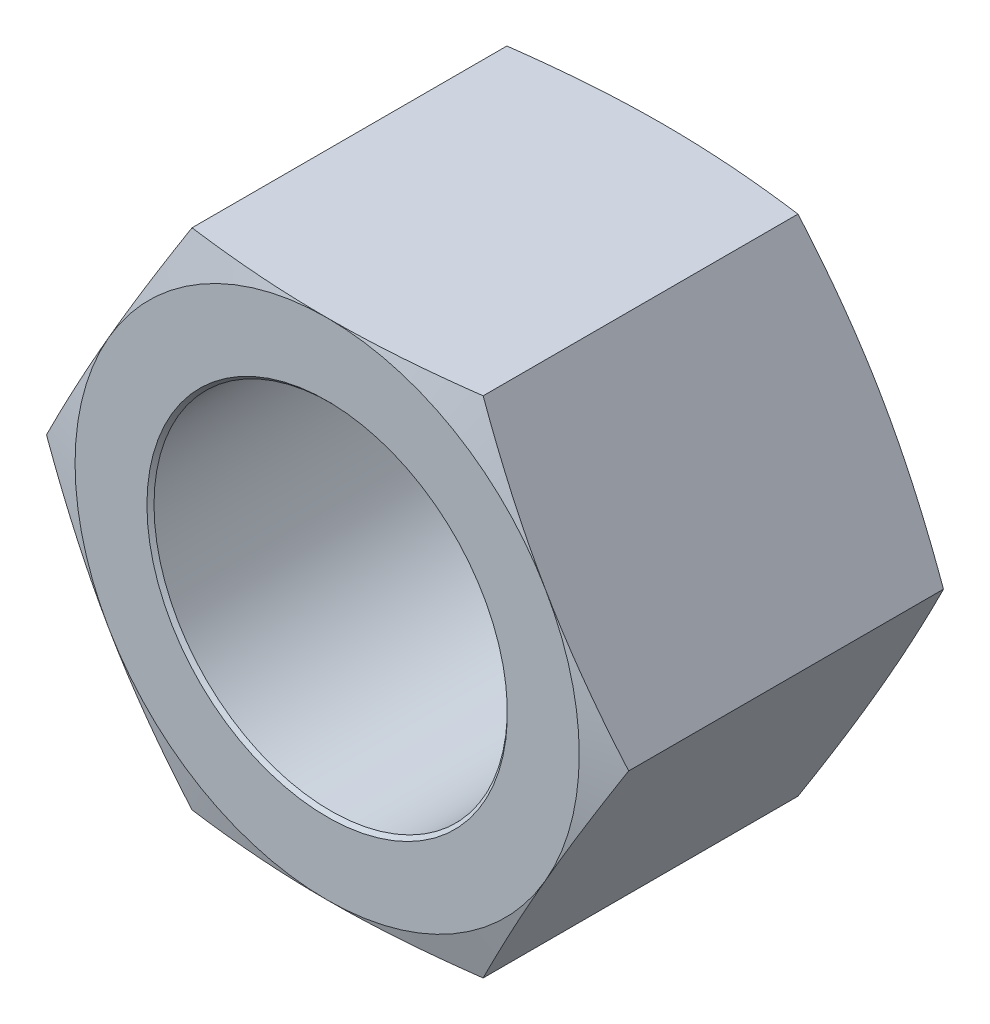
SolidWorks part; units mm, degrees
ref_plane "基准面1" through (0, 0, 0) normal (0, 0, 1) x (1, 0, 0)
ref_plane "基准面2" through (0, 0, 0) normal (0, 1, 0) x (1, 0, 0)
ref_plane "基准面3" through (0, 0, 0) normal (1, 0, 0) x (0, 0, -1)
sketch "尺寸草图" plane through (0, 0, 0) normal (0, 0, 1) x (1, 0, 0)
  line L0 (0, 0) -> (24.1005, 0)
  point P3 (20, 0)
  point P4 (1.5, 0)
  point P5 (32.95, 0)
  point P6 (19, 0)
  point P7 (6.4, 0)
  point P8 (30, 0)
  dimension "D" = 20
  dimension "e" = 32.95
  dimension "P1" = 1.5
  dimension "m" = 19
  dimension "mw" = 6.4
  dimension "s" = 30
sketch "草图1" plane through (0, 0, 0) normal (0, 0, 1) x (1, 0, 0)
  line L0 (-26.8088, 0) -> (37.1748, 0) construction
  line L1 (0, 25.0215) -> (0, -25.0215) construction
  line L3 (8.2375, 14.2678) -> (-8.2375, 14.2678)
  line L4 (-8.2375, 14.2678) -> (-16.475, 0)
  line L5 (-16.475, 0) -> (-8.2375, -14.2678)
  line L6 (-8.2375, -14.2678) -> (8.2375, -14.2678)
  line L7 (8.2375, -14.2678) -> (16.475, 0)
  line L8 (16.475, 0) -> (8.2375, 14.2678)
  circle A0 centre (0, 0) radius 14.2678 construction
  circle A1 centre (0, 0) radius 10
  dimension "D" = 20
  dimension "e" = 32.95
extrude "基体-拉伸" add sketch "草图1" along normal blind 19
cosmetic thread "装饰螺纹线1" parameters "D2"=21
sketch "草图2" plane through (0, 0, 0) normal (0, 0, -1) x (-1, 0, 0)
  line L0 (-8.2375, 14.2678) -> (8.2375, 14.2678) construction
  circle A0 centre (0, 0) radius 14.2678
  circle A1 centre (0, 0) radius 10 construction
extrude "切除-拉伸1" cut sketch "草图2" against normal blind 38 draft 75 flip side to cut
sketch "草图3" plane through (0, 0, 19) normal (0, 0, 1) x (1, 0, 0)
  line L0 (16.475, 0) -> (8.2375, 14.2678) construction
  circle A0 centre (0, 0) radius 14.2678
extrude "切除-拉伸2" cut sketch "草图3" against normal blind 38 draft 75 flip side to cut
chamfer "倒角1" distance 0.2 angle 45 2 edges at (10, 0, 0) (10, 0, 19)
equation "\"e@草图1\" = \"e@尺寸草图\""
equation "\"D@草图1\" = \"D@尺寸草图\""
equation "\"m@基体-拉伸\" = \"m@尺寸草图\""
equation "\"D2@装饰螺纹线1\" = 1.05 * \"D@尺寸草图\""
